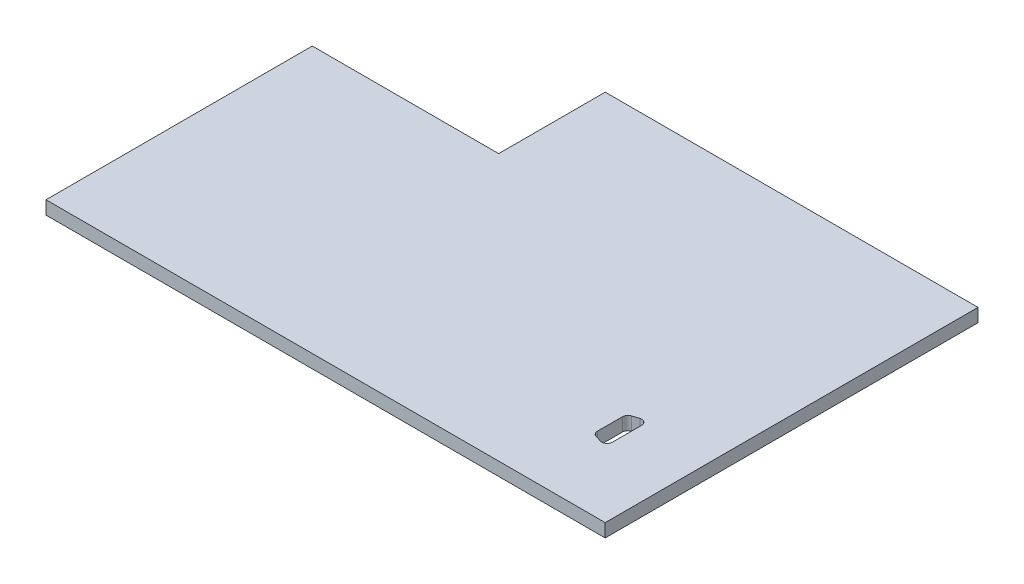
SolidWorks part; units mm, degrees
ref_plane "Front Plane" through (0, 0, 0) normal (0, 0, 1) x (1, 0, 0)
ref_plane "Top Plane" through (0, 0, 0) normal (0, 1, 0) x (1, 0, 0)
ref_plane "Right Plane" through (0, 0, 0) normal (1, 0, 0) x (0, 0, -1)
sketch "Sketch1" plane through (0, 0, 0) normal (0, 1, 0) x (1, 0, 0)
  line L0 (0, 0) -> (0, 127)
  line L3 (0, 127) -> (88.9, 127)
  line L4 (88.9, 127) -> (88.9, 177.8)
  line L5 (88.9, 177.8) -> (266.7, 177.8)
  line L6 (266.7, 177.8) -> (266.7, 0)
  line L7 (266.7, 0) -> (0, 0)
  dimension "D2" = 266.7
  dimension "D3" = 177.8
  dimension "D4" = 88.9
  dimension "D6" = 50.8
  dimension "D7" = 177.8
extrude "Boss-Extrude1" add sketch "Sketch1" along normal blind 6.35
sketch "Sketch2" plane through (0, 6.35, 0) normal (0, 1, 0) x (1, 0, 0)
  line L0 (19.05, 114.3) -> (101.6, 114.3)
  line L1 (101.6, 114.3) -> (101.6, 158.75)
  line L2 (19.05, 114.3) -> (19.05, 127)
  line L3 (88.9, 127) -> (0, 127) construction
  line L4 (19.05, 127) -> (88.9, 127)
  line L5 (88.9, 127) -> (88.9, 158.75)
  line L6 (88.9, 158.75) -> (101.6, 158.75)
  line L10 (88.9, 177.8) -> (88.9, 127) construction
  line L11 (88.9, 127) -> (0, 127) construction
  line L14 (0, 127) -> (0, 0) construction
  line L15 (266.7, 177.8) -> (88.9, 177.8) construction
  dimension "D1" = 19.05
  dimension "D2" = 19.05
  dimension "D5" = 12.7
  dimension "D6" = 12.7
extrude "Boss-Extrude2" add sketch "Sketch2" against normal blind 11.43
sketch "Sketch3" plane through (0, 6.35, 0) normal (0, 1, 0) x (1, 0, 0)
  line L0 (235.204, 31.496) -> (235.204, 52.324)
  line L1 (235.204, 52.324) -> (227.076, 49.784)
  line L2 (227.076, 49.784) -> (227.076, 34.036)
  line L3 (227.076, 34.036) -> (235.204, 31.496)
  line L4 (0, 0) -> (266.7, 0) construction
  line L5 (266.7, 0) -> (266.7, 177.8) construction
  dimension "D1" = 31.496
  dimension "D2" = 31.496
  dimension "D3" = 20.828
  dimension "D4" = 15.748
  dimension "D5" = 2.54
  dimension "D6" = 8.128
extrude "Cut-Extrude1" cut sketch "Sketch3" against normal blind 12.7
fillet "Fillet1" radius 2.54 4 edges at (235.204, 3.175, -31.496) (227.076, 3.175, -34.036) (235.204, 3.175, -52.324) (227.076, 3.175, -49.784)
